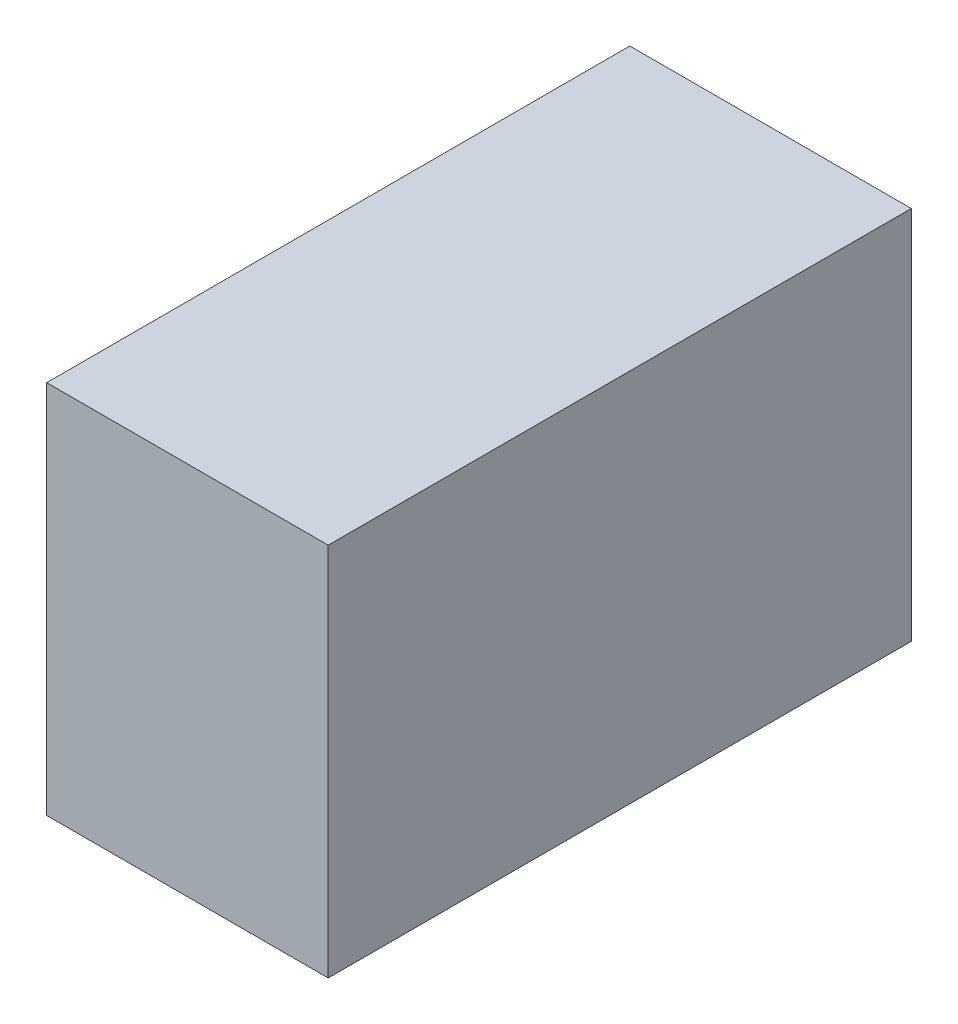
SolidWorks part; units mm, degrees
ref_plane "Front Plane" through (0, 0, 0) normal (0, 0, 1) x (1, 0, 0)
ref_plane "Top Plane" through (0, 0, 0) normal (0, 1, 0) x (1, 0, 0)
ref_plane "Right Plane" through (0, 0, 0) normal (1, 0, 0) x (0, 0, -1)
sketch "Sketch1" plane through (0, 0, 0) normal (0, 1, 0) x (1, 0, 0)
  line L1 (-9.8, -20.3) -> (9.8, -20.3)
  line L2 (-9.8, -20.3) -> (-9.8, 20.3)
  line L3 (-9.8, 20.3) -> (9.8, 20.3)
  line L4 (9.8, -20.3) -> (9.8, 20.3)
  line L5 (-9.8, -20.3) -> (9.8, 20.3) construction
  line L6 (-9.8, 20.3) -> (9.8, -20.3) construction
  point P0 (0, 0)
  dimension "D1" = 19.6
  dimension "D2" = 40.6
extrude "Boss-Extrude1" add sketch "Sketch1" along normal blind 26.1 contours L2 L3 L4 L1
